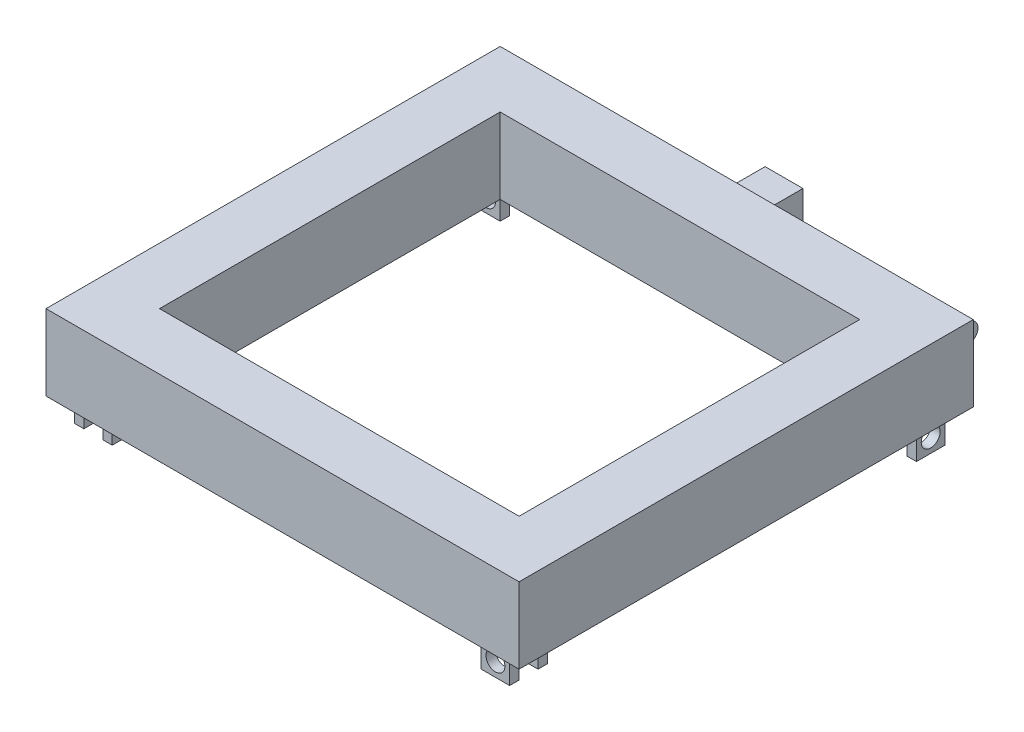
SolidWorks part; units mm, degrees
ref_plane "Front Plane" through (0, 0, 0) normal (0, 0, 1) x (1, 0, 0)
ref_plane "Top Plane" through (0, 0, 0) normal (0, 1, 0) x (1, 0, 0)
ref_plane "Right Plane" through (0, 0, 0) normal (1, 0, 0) x (0, 0, -1)
sketch "Sketch1" plane through (0, 0, 0) normal (0, 1, 0) x (1, 0, 0)
  line L0 (0, 0) -> (1270, 0)
  line L1 (1270, 0) -> (1270, -1219.2)
  line L2 (1270, -1219.2) -> (0, -1219.2)
  line L3 (0, -1219.2) -> (0, 0)
extrude "Boss-Extrude1" add sketch "Sketch1" along normal blind 203.2
sketch "Sketch2" plane through (0, 203.2, 0) normal (0, 1, 0) x (1, 0, 0)
  line L0 (0, 0) -> (0, -152.4)
  line L1 (0, 0) -> (0, -1219.2) construction
  line L2 (0, -152.4) -> (152.4, -152.4)
  line L3 (152.4, -152.4) -> (152.4, -1066.8)
  line L4 (152.4, -1066.8) -> (1117.6, -1066.8)
  line L5 (1117.6, -1066.8) -> (1117.6, -152.4)
  line L6 (1117.6, -152.4) -> (152.4, -152.4)
extrude "Cut-Extrude2" cut sketch "Sketch2" against normal blind 203.2 contours L5 L6 L3 L4
sketch "Sketch4" plane through (0, 0, 0) normal (0, -1, 0) x (-1, 0, 0)
  line L0 (0, -1219.2) -> (-127, -1219.2)
  line L1 (0, -1219.2) -> (-1270, -1219.2) construction
  line L2 (-127, -1219.2) -> (-127, -1092.2)
  line L3 (-127, -1092.2) -> (-101.6, -1092.2)
  line L4 (-101.6, -1092.2) -> (-101.6, -1168.4)
  line L5 (-101.6, -1168.4) -> (-127, -1168.4)
  line L6 (-127, -1168.4) -> (-50.8, -1168.4)
  line L7 (-50.8, -1168.4) -> (-50.8, -1092.2)
  line L8 (-50.8, -1092.2) -> (-25.4, -1092.2)
  line L9 (-25.4, -1092.2) -> (-25.4, -1168.4)
  line L10 (-25.4, -1168.4) -> (-50.8, -1168.4)
  line L11 (-1270, -1219.2) -> (-1270, -1092.2)
  line L12 (-1270, -1219.2) -> (-1270, 0) construction
  line L13 (-1270, -1092.2) -> (-1143, -1092.2)
  line L14 (-1143, -1092.2) -> (-1143, -1117.6)
  line L15 (-1143, -1117.6) -> (-1219.2, -1117.6)
  line L16 (-1219.2, -1117.6) -> (-1219.2, -1092.2)
  line L17 (-1219.2, -1092.2) -> (-1219.2, -1168.4)
  line L18 (-1219.2, -1168.4) -> (-1143, -1168.4)
  line L19 (-1143, -1168.4) -> (-1143, -1193.8)
  line L20 (-1143, -1193.8) -> (-1219.2, -1193.8)
  line L21 (-1219.2, -1193.8) -> (-1219.2, -1168.4)
  line L22 (-1270, 0) -> (-1143, 0)
  line L23 (-1270, 0) -> (0, 0) construction
  line L24 (-1143, 0) -> (-1143, -127)
  line L25 (-1143, -127) -> (-1168.4, -127)
  line L26 (-1168.4, -127) -> (-1168.4, -50.8)
  line L27 (-1168.4, -50.8) -> (-1143, -50.8)
  line L28 (-1143, -50.8) -> (-1219.2, -50.8)
  line L29 (-1219.2, -50.8) -> (-1219.2, -127)
  line L30 (-1219.2, -127) -> (-1244.6, -127)
  line L31 (-1244.6, -127) -> (-1244.6, -50.8)
  line L32 (-1244.6, -50.8) -> (-1219.2, -50.8)
  line L33 (0, 0) -> (0, -127)
  line L34 (0, 0) -> (0, -1219.2) construction
  line L35 (0, -127) -> (-127, -127)
  line L36 (-127, -127) -> (-127, -101.6)
  line L37 (-127, -101.6) -> (-50.8, -101.6)
  line L38 (-50.8, -101.6) -> (-50.8, -127)
  line L39 (-50.8, -127) -> (-50.8, -50.8)
  line L40 (-50.8, -50.8) -> (-127, -50.8)
  line L41 (-127, -50.8) -> (-127, -25.4)
  line L42 (-127, -25.4) -> (-50.8, -25.4)
  line L43 (-50.8, -25.4) -> (-50.8, -50.8)
extrude "Boss-Extrude2" add sketch "Sketch4" along normal blind 76.2 contours L10 L9 L8 L7 | L5 L4 L3 L2 | L21 L20 L19 L18 | L16 L15 L14 L13 | L32 L31 L30 L29 | L27 L26 L25 L24 | L38 L37 L36 L35 | L43 L42 L41 L40
sketch "Sketch6" plane through (25.4, 0, 0) normal (-1, 0, 0) x (0, 0, 1)
  line L0 (1130.3, -76.2) -> (1130.3, -38.1)
  line L1 (1092.2, -76.2) -> (1168.4, -76.2) construction
  circle A1 centre (1130.3, -38.1) radius 25.4
extrude "Cut-Extrude3" cut sketch "Sketch6" against normal blind 127
sketch "Sketch7" plane through (0, 0, 1193.8) normal (0, 0, 1) x (1, 0, 0)
  line L0 (1181.1, -76.2) -> (1181.1, -38.1)
  line L1 (1143, -76.2) -> (1219.2, -76.2) construction
  circle A0 centre (1181.1, -38.1) radius 25.4
extrude "Cut-Extrude4" cut sketch "Sketch7" against normal blind 127
sketch "Sketch8" plane through (1244.6, 0, 0) normal (1, 0, 0) x (0, 0, -1)
  line L0 (-88.9, -76.2) -> (-88.9, -38.1)
  line L1 (-127, -76.2) -> (-50.8, -76.2) construction
  circle A0 centre (-88.9, -38.1) radius 25.4
extrude "Cut-Extrude5" cut sketch "Sketch8" against normal blind 127
sketch "Sketch9" plane through (0, 0, 25.4) normal (0, 0, -1) x (-1, 0, 0)
  line L0 (-88.9, 0) -> (-88.9, -38.1)
  line L1 (-127, 0) -> (-50.8, 0) construction
  circle A0 centre (-88.9, -38.1) radius 25.4
extrude "Cut-Extrude6" cut sketch "Sketch9" against normal blind 127
sketch "Sketch10" plane through (0, 0, 0) normal (0, 0, -1) x (-1, 0, 0)
  line L0 (-635, 203.2) -> (-635, 101.6)
  line L1 (-1270, 203.2) -> (0, 203.2) construction
  line L2 (-635, 152.4) -> (-584.2, 152.4)
  line L3 (-584.2, 152.4) -> (-584.2, 50.8)
  line L4 (-584.2, 50.8) -> (-685.8, 50.8)
  line L5 (-685.8, 50.8) -> (-685.8, 152.4)
  line L6 (-685.8, 152.4) -> (-635, 152.4)
extrude "Boss-Extrude3" add sketch "Sketch10" along normal blind 127
sketch "Sketch11" plane through (584.2, 0, 0) normal (-1, 0, 0) x (0, 0, 1)
  line L0 (-63.5, 152.4) -> (-63.5, 101.6)
  line L1 (-127, 152.4) -> (0, 152.4) construction
  circle A0 centre (-63.5, 101.6) radius 25.4
extrude "Boss-Extrude4" add sketch "Sketch11" along normal blind 508
sketch "Sketch12" plane through (685.8, 0, 0) normal (1, 0, 0) x (0, 0, -1)
  line L0 (63.5, 152.4) -> (63.5, 101.6)
  line L1 (127, 152.4) -> (0, 152.4) construction
  circle A0 centre (63.5, 101.6) radius 25.4
extrude "Boss-Extrude5" add sketch "Sketch12" along normal blind 508
